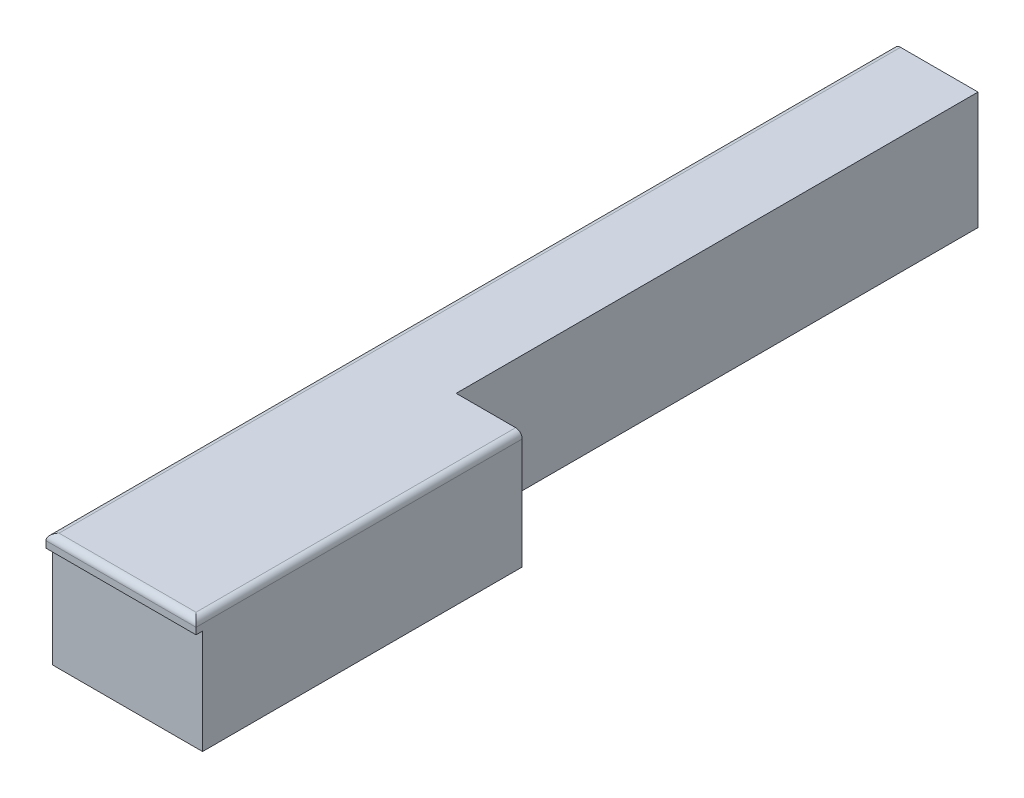
SolidWorks part; units mm, degrees
material "Pino"
ref_plane "Alzado" through (0, 0, 0) normal (0, 0, 1) x (1, 0, 0)
ref_plane "Planta" through (0, 0, 0) normal (0, 1, 0) x (1, 0, 0)
ref_plane "Vista lateral" through (0, 0, 0) normal (1, 0, 0) x (0, 0, -1)
sketch "Croquis2" plane through (0, 0, 0) normal (0, 1, 0) x (1, 0, 0)
  line L1 (0, 0) -> (23, 0)
  line L2 (0, 0) -> (0, 130)
  line L3 (0, 130) -> (23, 130)
  line L4 (23, 0) -> (23, 130)
  line L5 (23, 50) -> (12.875, 50)
  line L6 (23, 50) -> (23, 130)
  line L7 (23, 130) -> (12.875, 130)
  line L8 (12.875, 50) -> (12.875, 130)
  dimension "D1" = 23
  dimension "D2" = 130
  dimension "D3" = 12.875
  dimension "D4" = 50
extrude "Saliente-Extruir1" add sketch "Croquis2" along normal blind 18
sketch "Croquis3" plane through (0, 0, 0) normal (0, 0, 1) x (1, 0, 0)
  line L0 (23, 18) -> (23, 0) construction
  line L1 (0, 0) -> (23, 0)
  line L2 (0, 0) -> (0, 16)
  line L3 (0, 16) -> (23, 16)
  line L4 (23, 0) -> (23, 16)
  line L5 (0, 18) -> (23, 18) construction
  dimension "D1" = 2
extrude "Cortar-Extruir1" cut sketch "Croquis3" against normal blind 1
fillet "Redondeo4" radius 1 3 edges at (11.5, 18, 0) (0, 18, -65) (23, 18, -25)
